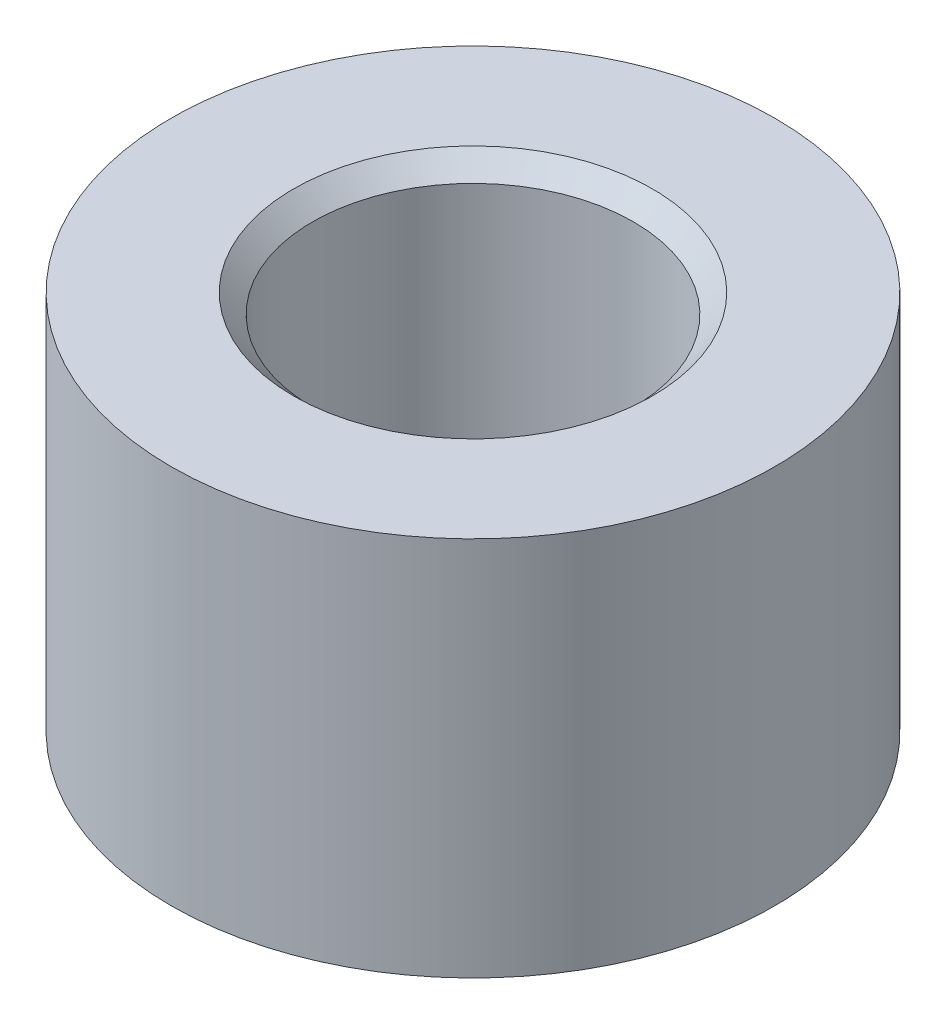
SolidWorks part; units mm, degrees
ref_plane "Front Plane" through (0, 0, 0) normal (0, 0, 1) x (1, 0, 0)
ref_plane "Top Plane" through (0, 0, 0) normal (0, 1, 0) x (1, 0, 0)
ref_plane "Right Plane" through (0, 0, 0) normal (1, 0, 0) x (0, 0, -1)
sketch "Sketch1" plane through (0, 0, 0) normal (0, 1, 0) x (1, 0, 0)
  circle A0 centre (0, 0) radius 6.35
  circle A1 centre (0, 0) radius 3.375
  dimension "D1" = 6.75
  dimension "D2" = 12.7
extrude "Boss-Extrude1" add sketch "Sketch1" along normal blind 8.001
chamfer "Chamfer1" distance 0.4 angle 45 2 edges at (0, 0, 3.375) (0, 8.001, 3.375)
